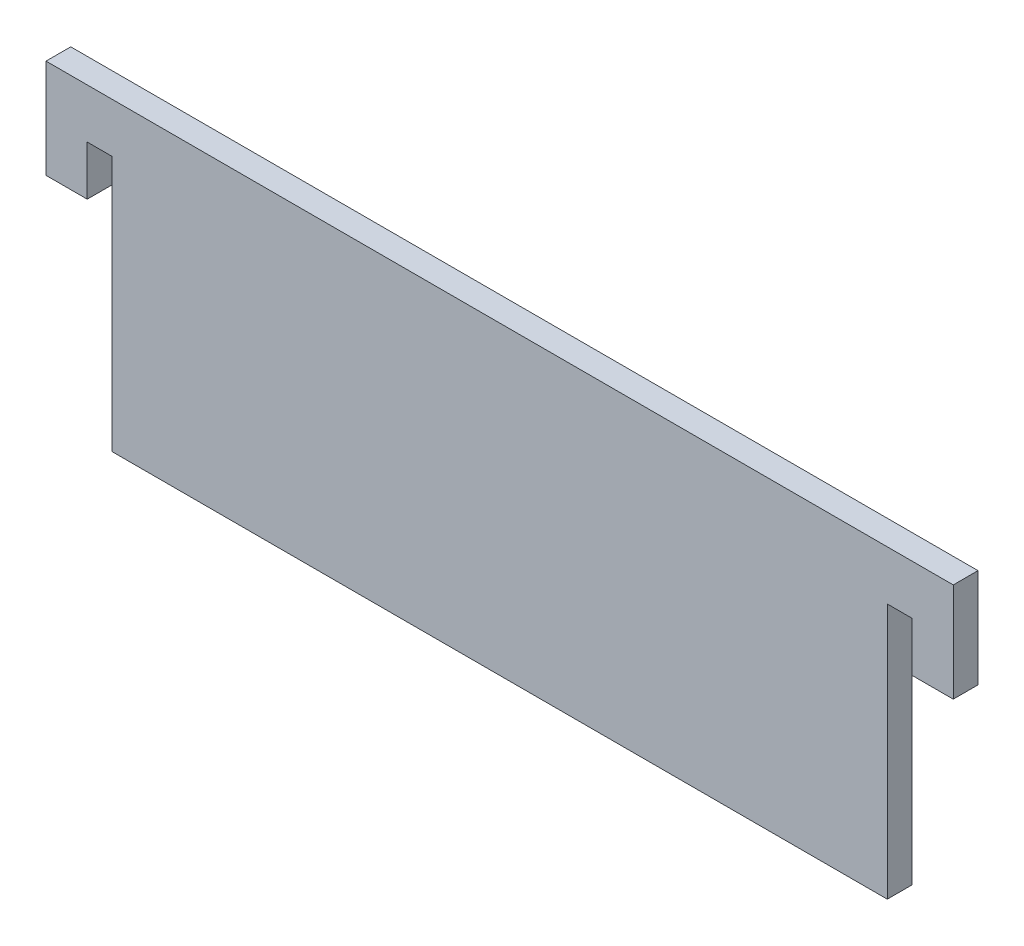
SolidWorks part; units mm, degrees
ref_plane "前基準面" through (0, 0, 0) normal (0, 0, 1) x (1, 0, 0)
ref_plane "上基準面" through (0, 0, 0) normal (0, 1, 0) x (1, 0, 0)
ref_plane "右基準面" through (0, 0, 0) normal (1, 0, 0) x (0, 0, -1)
sketch "草圖1" plane through (0, 0, 0) normal (0, 0, 1) x (1, 0, 0)
  line L0 (-41.7371, 15.4598) -> (-32.7371, 15.4598)
  line L2 (-41.7371, 15.4598) -> (-41.7371, 1.9598)
  line L3 (-41.7371, -21.5402) -> (-32.7371, -21.5402)
  line L4 (58.2629, 15.4598) -> (58.2629, 1.9598)
  line L13 (8.2629, 15.4598) -> (8.2629, -14.5402) construction
  line L14 (-22.7371, 15.4598) -> (-22.7371, 12.4598)
  line L16 (1.2629, 15.4598) -> (1.2629, 12.4598)
  line L17 (1.2629, 12.4598) -> (-8.7371, 12.4598)
  line L18 (-8.7371, 15.4598) -> (-8.7371, 12.4598)
  line L20 (-32.7371, 15.4598) -> (-32.7371, 12.4598)
  line L21 (-22.7371, 12.4598) -> (-32.7371, 12.4598)
  line L23 (-37.2697, 15.4598) -> (-41.7371, 15.4598)
  line L26 (-56.7371, 15.4598) -> (-56.7371, 12.4598) [skipped]
  line L27 (58.2629, -8.0402) -> (55.2629, -8.0402)
  line L28 (-41.7371, 1.9598) -> (-38.7371, 1.9598)
  line L29 (-41.7371, 15.4598) -> (-41.7371, 1.9598)
  line L31 (49.2629, 15.4598) -> (49.2629, 12.4598)
  line L32 (39.2629, 12.4598) -> (49.2629, 12.4598)
  line L33 (39.2629, 15.4598) -> (39.2629, 12.4598)
  line L34 (15.2629, 12.4598) -> (25.2629, 12.4598)
  line L35 (25.2629, 15.4598) -> (25.2629, 12.4598)
  line L37 (15.2629, 15.4598) -> (15.2629, 12.4598)
  line L38 (-38.7371, -3.0402) -> (55.2629, -3.0402) construction
  line L40 (-41.7371, -8.0402) -> (-38.7371, -8.0402)
  line L41 (39.2629, -21.5402) -> (39.2629, -18.5402)
  line L42 (39.2629, -18.5402) -> (49.2629, -18.5402)
  line L43 (49.2629, -21.5402) -> (49.2629, -18.5402)
  line L45 (15.2629, -21.5402) -> (15.2629, -18.5402)
  line L47 (25.2629, -21.5402) -> (25.2629, -18.5402)
  line L48 (15.2629, -18.5402) -> (25.2629, -18.5402)
  line L49 (1.2629, -18.5402) -> (-8.7371, -18.5402)
  line L50 (-8.7371, -21.5402) -> (-8.7371, -18.5402)
  line L52 (1.2629, -21.5402) -> (1.2629, -18.5402)
  line L54 (-32.7371, -21.5402) -> (-32.7371, -18.5402)
  line L55 (-22.7371, -18.5402) -> (-32.7371, -18.5402)
  line L56 (-22.7371, -21.5402) -> (-22.7371, -18.5402)
  line L57 (-38.7371, 1.9598) -> (-38.7371, -8.0402)
  line L58 (55.2629, 1.9598) -> (55.2629, -8.0402)
  line L59 (-38.4802, 12.4598) -> (-43.4802, 12.4598) [skipped]
  line L60 (-46.7371, 15.4598) -> (-46.7371, 12.4598) [skipped]
  line L61 (58.2629, 1.9598) -> (55.2629, 1.9598)
  line L63 (-41.7371, -8.0402) -> (-41.7371, -21.5402)
  line L64 (-41.7371, -8.0402) -> (-41.7371, -21.5402)
  line L65 (58.2629, -8.0402) -> (58.2629, -21.5402)
  line L66 (49.2629, 15.4598) -> (58.2629, 15.4598)
  line L67 (25.2629, 15.4598) -> (39.2629, 15.4598)
  line L68 (1.2629, 15.4598) -> (15.2629, 15.4598)
  line L69 (-22.7371, 15.4598) -> (-8.7371, 15.4598)
  line L70 (-22.7371, -21.5402) -> (-8.7371, -21.5402)
  line L71 (1.2629, -21.5402) -> (15.2629, -21.5402)
  line L72 (25.2629, -21.5402) -> (39.2629, -21.5402)
  line L73 (49.2629, -21.5402) -> (58.2629, -21.5402)
  point P19 (-38.7371, -3.0402)
  dimension "D1" = 37
  dimension "D2" = 100
  dimension "D3" = 3
  dimension "D4" = 10
  dimension "D5" = 7
  dimension "D7" = 3
  dimension "D8" = 10
  dimension "D9" = 14
  dimension "D6" = 3
extrude "填料-伸長1" add sketch "草圖1" along normal blind 3 contours L43 L73 L65 L27 L58 L61 L4 L66 L31 L32 L33 L67 L35 L34 L37 L68 L16 L17 L18 L69 L14 L21 L20 L0 L2 L28 L57 L40 L63 L3 L54 L55 L56 L70 L50 L49 L52 L71 L45 L48 L47 L72 L41 L42
sketch "草圖2" plane through (0, 0, 3) normal (0, 0, 1) x (1, 0, 0)
  line L1 (-41.7371, -21.5402) -> (58.2629, -21.5402)
  line L2 (-41.7371, -21.5402) -> (-41.7371, 15.4598)
  line L3 (-41.7371, 15.4598) -> (58.2629, 15.4598)
  line L4 (58.2629, -21.5402) -> (58.2629, 15.4598)
extrude "填料-伸長2" add sketch "草圖2" against normal blind 3
sketch "草圖3" plane through (0, 0, 3) normal (0, 0, 1) x (1, 0, 0)
  line L0 (8.2629, 15.4598) -> (8.2629, -2.3476) construction
  line L1 (-41.7371, 15.4598) -> (58.2629, 15.4598) construction
  line L2 (58.2629, 3.4598) -> (63.2629, 3.4598)
  line L3 (-41.7371, 15.4598) -> (-46.7371, 15.4598)
  line L4 (-41.7371, 15.4598) -> (-41.7371, 3.4598)
  line L5 (-41.7371, 3.4598) -> (-46.7371, 3.4598)
  line L6 (-46.7371, 15.4598) -> (-46.7371, 3.4598)
  line L7 (63.2629, 15.4598) -> (63.2629, 3.4598)
  line L8 (58.2629, 15.4598) -> (63.2629, 15.4598)
  line L9 (58.2629, 15.4598) -> (58.2629, 3.4598)
  dimension "D1" = 5
  dimension "D2" = 12
extrude "填料-伸長3" add sketch "草圖3" against normal blind 3
sketch "草圖4" plane through (0, 0, 3) normal (0, 0, 1) x (1, 0, 0)
  line L0 (-46.7371, 15.4598) -> (63.2629, 15.4598) construction
  line L1 (-41.7371, -21.5402) -> (-38.7371, -21.5402)
  line L2 (-41.7371, -21.5402) -> (-41.7371, 9.4598)
  line L3 (-41.7371, 9.4598) -> (-38.7371, 9.4598)
  line L4 (-38.7371, -21.5402) -> (-38.7371, 9.4598)
  line L5 (8.2629, 15.4598) -> (8.2629, 1.1853) construction
  line L6 (58.2629, 9.4598) -> (55.2629, 9.4598)
  line L7 (55.2629, -21.5402) -> (55.2629, 9.4598)
  line L8 (58.2629, -21.5402) -> (55.2629, -21.5402)
  line L9 (58.2629, -21.5402) -> (58.2629, 9.4598)
  dimension "D1" = 3
  dimension "D2" = 6
extrude "除料-伸長1" cut sketch "草圖4" against normal blind 3
